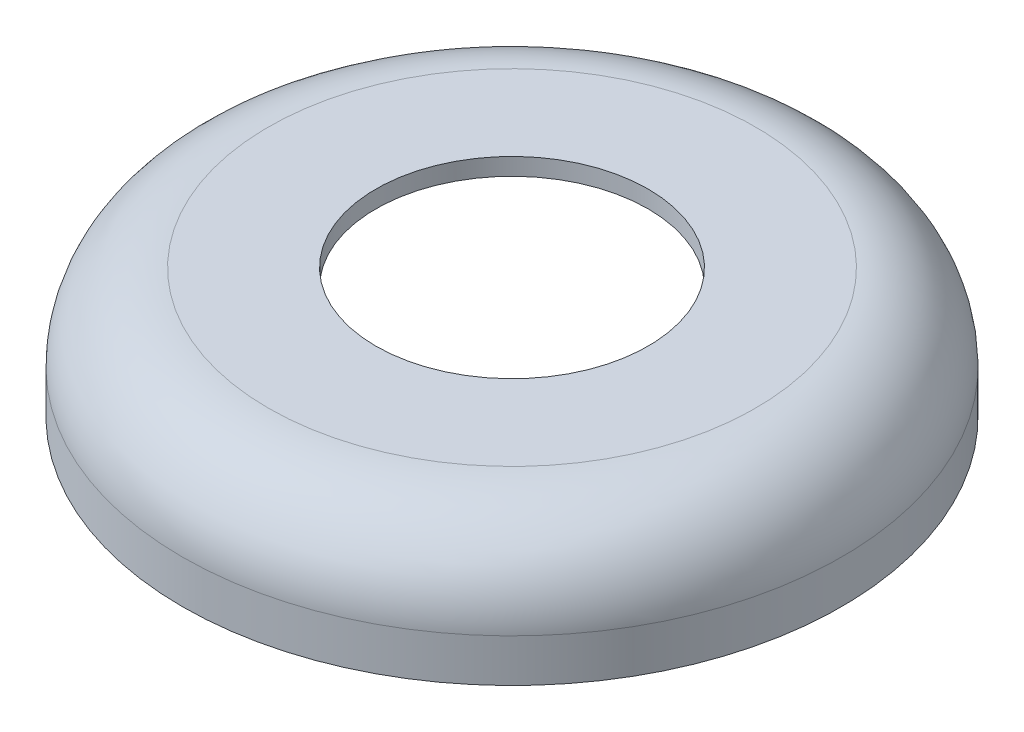
SolidWorks part; units mm, degrees
material "Nickel"
ref_plane "Front Plane" through (0, 0, 0) normal (0, 0, 1) x (1, 0, 0)
ref_plane "Top Plane" through (0, 0, 0) normal (0, 1, 0) x (1, 0, 0)
ref_plane "Right Plane" through (0, 0, 0) normal (1, 0, 0) x (0, 0, -1)
sketch "Sketch2" plane through (0, 0, 0) normal (0, 1, 0) x (1, 0, 0)
  circle A0 centre (0, 0) radius 11.5
  dimension "D1" = 23
extrude "Boss-Extrude1" add sketch "Sketch2" along normal blind 4.5
fillet "Fillet1" radius 3 1 edges at (0, 4.5, 11.5)
shell "Shell1" thickness 0.6
sketch "Sketch3" plane through (0, 4.5, 0) normal (0, 1, 0) x (1, 0, 0)
  circle A0 centre (0, 0) radius 4.75
  dimension "D1" = 9.5
extrude "Cut-Extrude1" cut sketch "Sketch3" against normal through all
